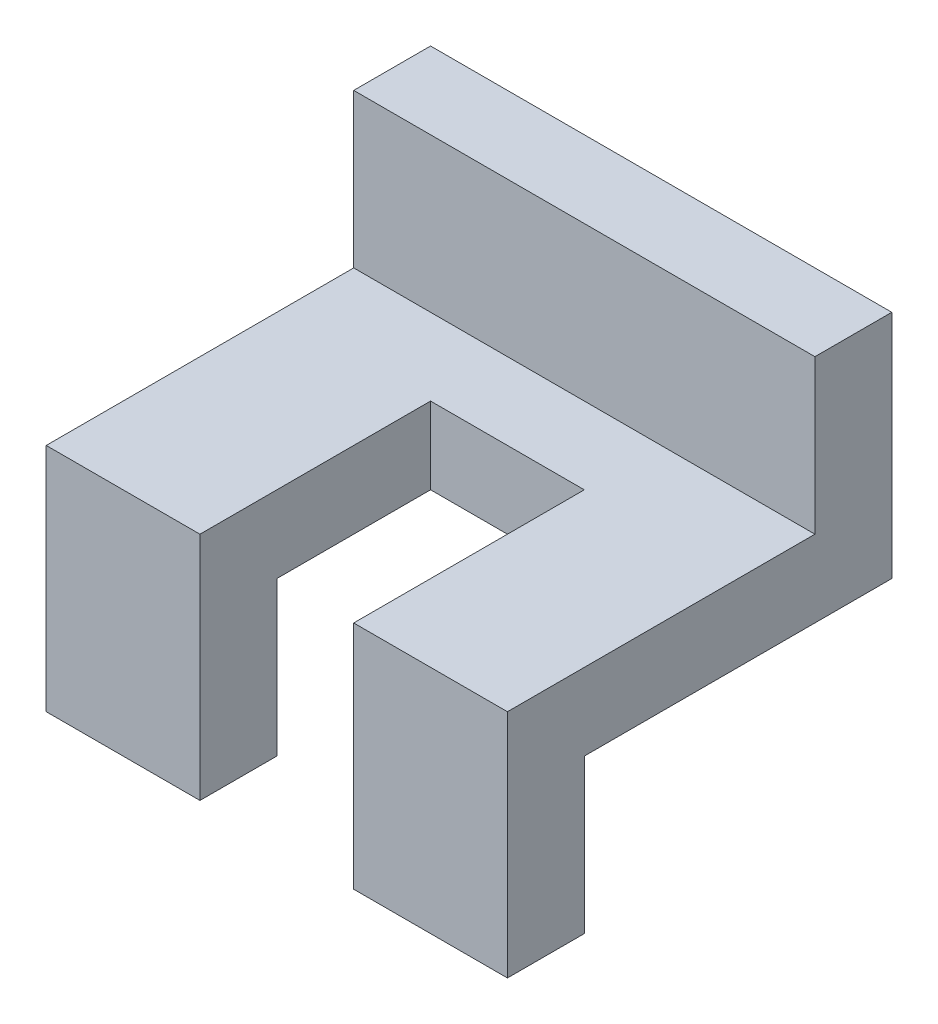
SolidWorks part; units mm, degrees
ref_plane "Front Plane" through (0, 0, 0) normal (0, 0, 1) x (1, 0, 0)
ref_plane "Top Plane" through (0, 0, 0) normal (0, 1, 0) x (1, 0, 0)
ref_plane "Right Plane" through (0, 0, 0) normal (1, 0, 0) x (0, 0, -1)
sketch "Sketch1" plane through (0, 0, 0) normal (1, 0, 0) x (0, 0, -1)
  line L0 (0, 0) -> (0, 19.05)
  line L1 (0, 19.05) -> (25.4, 19.05)
  line L2 (25.4, 19.05) -> (25.4, 31.75)
  line L3 (25.4, 31.75) -> (31.75, 31.75)
  line L4 (31.75, 31.75) -> (31.75, 12.7)
  line L5 (31.75, 12.7) -> (6.35, 12.7)
  line L6 (6.35, 12.7) -> (6.35, 0)
  line L7 (6.35, 0) -> (0, 0)
  dimension "D1" = 6.35
  dimension "D2" = 31.75
  dimension "D3" = 6.35
  dimension "D4" = 12.7
  dimension "D5" = 31.75
  dimension "D6" = 6.35
extrude "Boss-Extrude1" add sketch "Sketch1" along normal mid plane 38.1
sketch "Sketch2" plane through (0, 19.05, 0) normal (0, 1, 0) x (1, 0, 0)
  line L1 (-6.35, 0) -> (6.35, 0)
  line L2 (-6.35, 0) -> (-6.35, 19.05)
  line L3 (-6.35, 19.05) -> (6.35, 19.05)
  line L4 (-19.05, 25.4) -> (-19.05, 0)
  line L5 (-19.05, 0) -> (19.05, 0)
  line L6 (19.05, 0) -> (19.05, 25.4)
  line L7 (19.05, 25.4) -> (-19.05, 25.4)
  line L8 (-19.05, 25.4) -> (-19.05, 0)
  line L9 (-19.05, 0) -> (19.05, 0)
  line L10 (19.05, 0) -> (19.05, 25.4)
  line L11 (19.05, 25.4) -> (-19.05, 25.4)
  line L12 (6.35, 0) -> (6.35, 19.05)
  line L13 (-6.35, 0) -> (6.35, 19.05) construction
  line L14 (-6.35, 19.05) -> (6.35, 0) construction
  point P2 (0, 9.525)
  line M10 (-19.05, 0) -> (19.05, 0)
  dimension "D2" = 19.05
  dimension "D3" = 12.7
  dimension "D1" = 0
extrude "Cut-Extrude1" cut sketch "Sketch2" against normal through all and the other way blind 38.1 contours L12 L3 L2 M10
